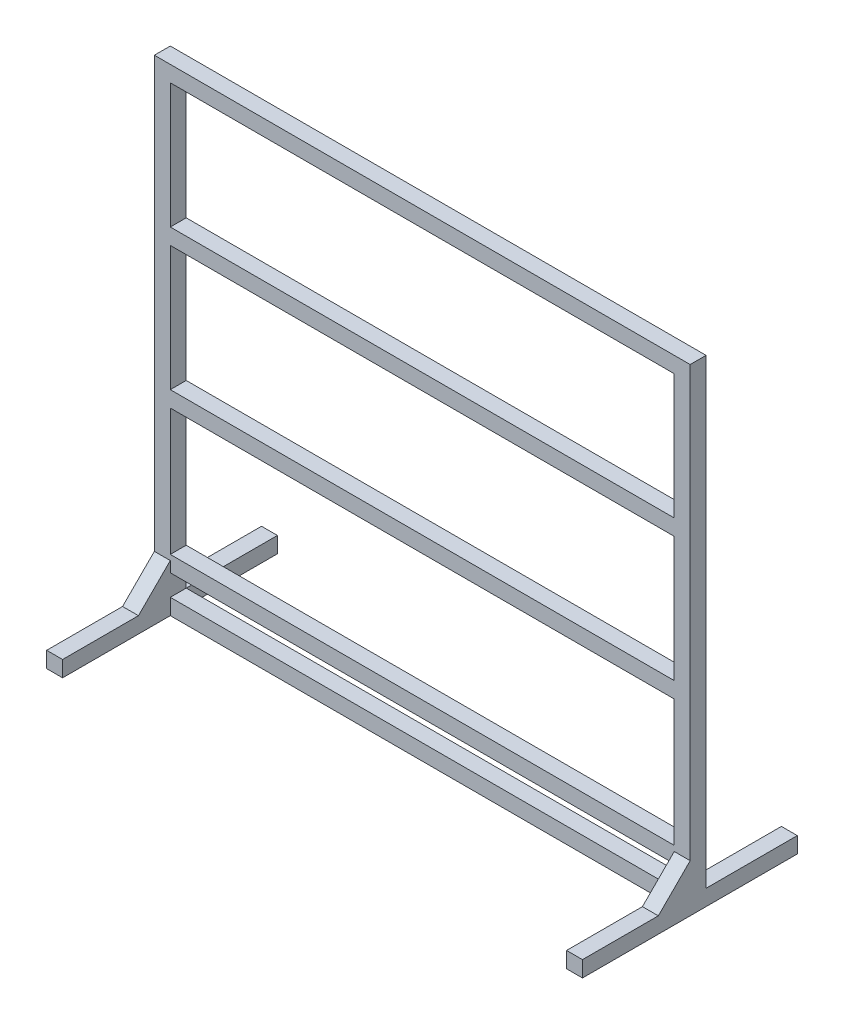
SolidWorks part; units mm, degrees
ref_plane "Front Plane" through (0, 0, 0) normal (0, 0, 1) x (1, 0, 0)
ref_plane "Top Plane" through (0, 0, 0) normal (0, 1, 0) x (1, 0, 0)
ref_plane "Right Plane" through (0, 0, 0) normal (1, 0, 0) x (0, 0, -1)
sketch "Sketch1" plane through (0, 0, 0) normal (0, 0, 1) x (1, 0, 0)
  line L0 (30, -30) -> (980, -30)
  line L1 (0, 0) -> (1010, 0)
  line L2 (0, 0) -> (0, -900)
  line L3 (0, -900) -> (1010, -900)
  line L4 (1010, 0) -> (1010, -900)
  line L5 (980, -30) -> (980, -870)
  line L6 (30, -870) -> (980, -870)
  line L7 (30, -30) -> (30, -870)
  line L8 (30, -265.5) -> (980, -265.5)
  line L9 (30, -295.5) -> (980, -295.5)
  line L10 (30, -531) -> (980, -531)
  line L11 (30, -561) -> (980, -561)
  line L12 (30, -800) -> (980, -800)
  line L13 (30, -830) -> (980, -830)
  dimension "D1" = 1010
  dimension "D2" = 900
  dimension "D5" = 295.5
  dimension "D7" = 295.5
  dimension "D9" = 100
  dimension "D3" = 30
  dimension "D4" = 30
  dimension "D6" = 30
  dimension "D8" = 30
extrude "Boss-Extrude1" add sketch "Sketch1" along normal blind 30 contours L4 L1 L2 L3 L7 L0 L5 L6 | L7 L13 L5 L12 | L7 L11 L5 L10 | L7 L9 L5 L8
sketch "Sketch2" plane through (0, 0, 30) normal (0, 0, 1) x (1, 0, 0)
  line L1 (30, -870) -> (0, -870)
  line L2 (30, -870) -> (30, -900)
  line L3 (30, -900) -> (0, -900)
  line L4 (0, -870) -> (0, -900)
  line L5 (980, -870) -> (1010, -870)
  line L6 (980, -870) -> (980, -900)
  line L7 (980, -900) -> (1010, -900)
  line L8 (1010, -870) -> (1010, -900)
extrude "Boss-Extrude2" add sketch "Sketch2" along normal blind 203
sketch "Sketch3" plane through (0, 0, 0) normal (0, 0, -1) x (-1, 0, 0)
  line L1 (-30, -870) -> (0, -870)
  line L2 (-30, -870) -> (-30, -900)
  line L3 (-30, -900) -> (0, -900)
  line L4 (0, -870) -> (0, -900)
  line L5 (-980, -870) -> (-1010, -870)
  line L6 (-980, -870) -> (-980, -900)
  line L7 (-980, -900) -> (-1010, -900)
  line L8 (-1010, -870) -> (-1010, -900)
extrude "Boss-Extrude3" add sketch "Sketch3" along normal blind 172
sketch "Sketch4" plane through (0, 0, 0) normal (-1, 0, 0) x (0, 0, 1)
  line L0 (30, -810) -> (90, -870)
  line L1 (30, 0) -> (30, -870) construction
  line L2 (233, -870) -> (30, -870) construction
  line L3 (90, -870) -> (30, -870)
  line L4 (30, -870) -> (30, -810)
  dimension "D1" = 60
  dimension "D2" = 60
extrude "Boss-Extrude4" add sketch "Sketch4" against normal blind 30
sketch "Sketch5" plane through (1010, 0, 0) normal (1, 0, 0) x (0, 0, -1)
  line L0 (-30, -810) -> (-30, -870)
  line L1 (-30, 0) -> (-30, -870) construction
  line L2 (-30, -870) -> (-90, -870)
  line L3 (-233, -870) -> (-30, -870) construction
  line L4 (-90, -870) -> (-30, -810)
  dimension "D1" = 60
  dimension "D2" = 60
extrude "Boss-Extrude5" add sketch "Sketch5" against normal blind 30
